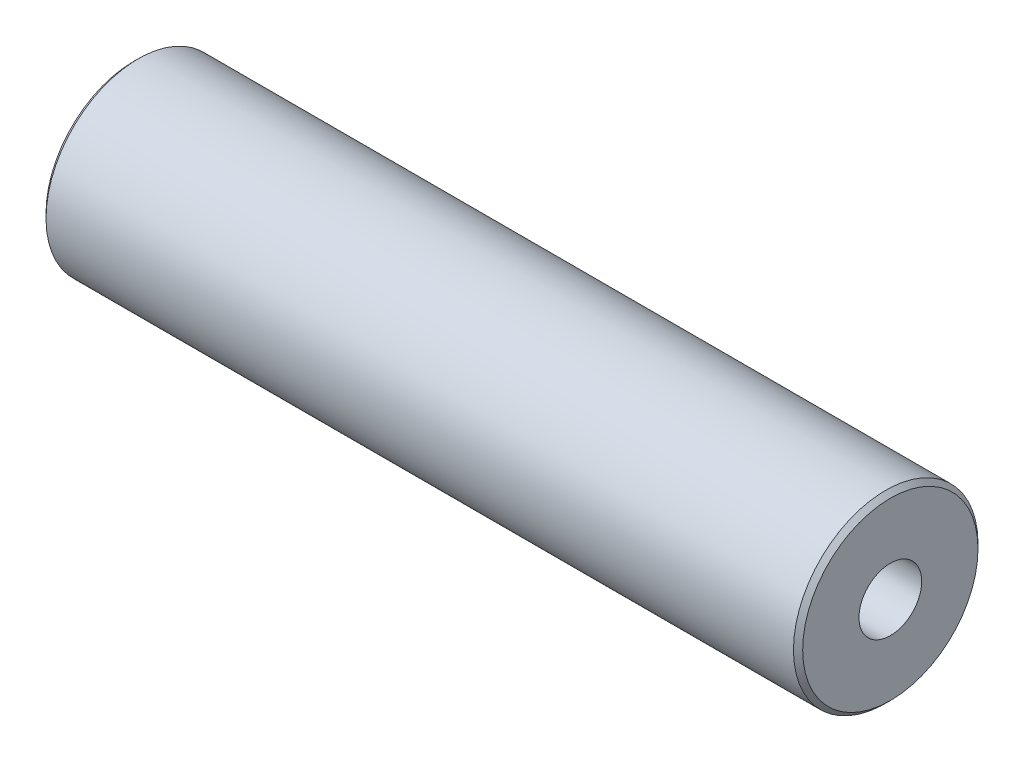
SolidWorks part; units mm, degrees
material "ALUMINIUM,  6082-T6"
ref_plane "Front Plane" through (0, 0, 0) normal (0, 0, 1) x (1, 0, 0)
ref_plane "Top Plane" through (0, 0, 0) normal (0, 1, 0) x (1, 0, 0)
ref_plane "Right Plane" through (0, 0, 0) normal (1, 0, 0) x (0, 0, -1)
sketch "Sketch1" plane through (0, 0, 0) normal (1, 0, 0) x (0, 0, -1)
  circle A0 centre (0, 0) radius 10
  dimension "D1" = 20
extrude "Boss-Extrude1" add sketch "Sketch1" along normal mid plane 82
chamfer "Chamfer1" distance 0.5 angle 45 2 edges at (41, 0, -10) (-41, 0, -10)
hole_wizard "M8 Tapped Hole1" positions "Sketch2" profile "Sketch3" tap size "M8" standard "ISO"
sketch "Sketch2" plane through (41, 0, 0) normal (1, 0, 0) x (0, 0, -1)
  point P0 (0, 0)
sketch "Sketch3" plane through (41, 0, 0) normal (0, 1, 0) x (0, 0, -1)
  line L0 (0, 0) -> (0, 24.2929)
  line L1 (0, 24.2929) -> (3.4, 22.25)
  line L2 (3.4, 22.25) -> (3.4, 0)
  line L5 (3.4, 0) -> (0, 0)
  line L10 (0, 24.2929) -> (-3.4, 22.25) construction
  line L11 (0, -6.35) -> (0, 107.95) construction
  dimension "Tap Drill Dia." = 6.8
  dimension "Tap Drill Depth" = 22.25
  dimension "Drill Angle" = 118
cosmetic thread "Hole Thread1"
hole_wizard "M8 Tapped Hole2" positions "Sketch4" profile "Sketch5" tap size "M8" standard "ISO"
sketch "Sketch4" plane through (-41, 0, 0) normal (-1, 0, 0) x (0, 0, 1)
  point P0 (0, 0)
sketch "Sketch5" plane through (-41, 0, 0) normal (0, 1, 0) x (0, 0, 1)
  line L0 (0, 0) -> (0, 24.2929)
  line L1 (0, 24.2929) -> (3.4, 22.25)
  line L2 (3.4, 22.25) -> (3.4, 0)
  line L5 (3.4, 0) -> (0, 0)
  line L10 (0, 24.2929) -> (-3.4, 22.25) construction
  line L11 (0, -6.35) -> (0, 107.95) construction
  dimension "Tap Drill Dia." = 6.8
  dimension "Tap Drill Depth" = 22.25
  dimension "Drill Angle" = 118
cosmetic thread "Hole Thread2" parameters "D1"=16, "D2"=8
